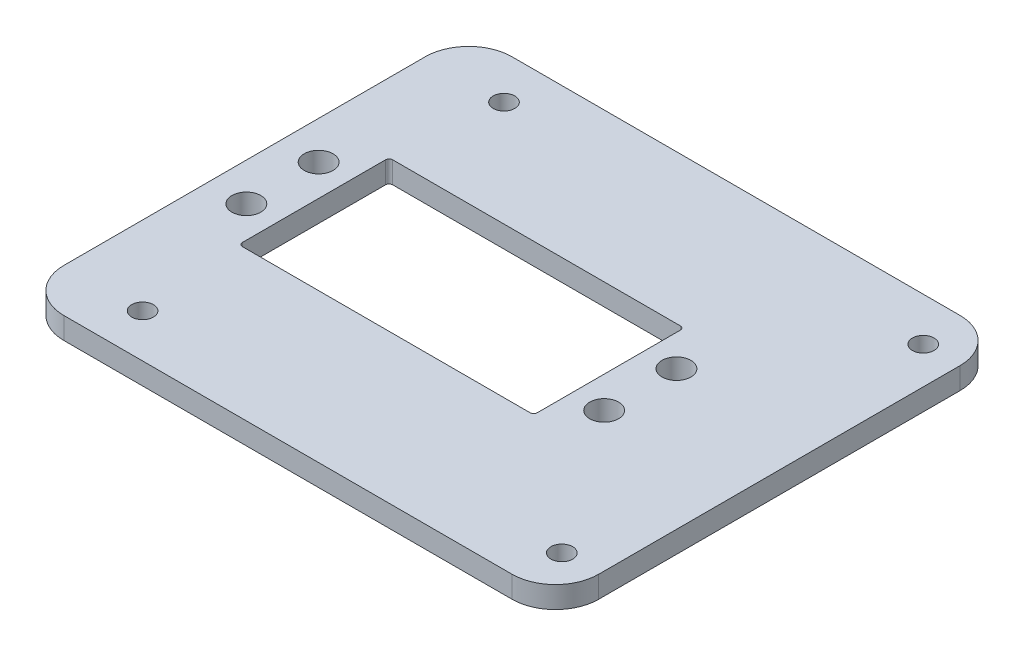
SolidWorks part; units mm, degrees
material "Thornel Mat VMA"
ref_plane "前视基准面" through (0, 0, 0) normal (0, 0, 1) x (1, 0, 0)
ref_plane "上视基准面" through (0, 0, 0) normal (0, 1, 0) x (1, 0, 0)
ref_plane "右视基准面" through (0, 0, 0) normal (1, 0, 0) x (0, 0, -1)
other "Configuration Table"
sketch "草图1" plane through (0, 0, 0) normal (0, 1, 0) x (1, 0, 0)
  line L0 (0, 0) -> (0, 29.6725) construction
  line L1 (-30, -31) -> (30, -31)
  line L2 (-30, -31) -> (-30, 31)
  line L3 (-30, 31) -> (30, 31)
  line L4 (30, -31) -> (30, 31)
  line L5 (-30, -31) -> (30, 31) construction
  line L6 (-30, 31) -> (30, -31) construction
  line L11 (-15.5388, -16.0567) -> (15.4817, 15.9977) construction
  line L12 (9.89, 0) -> (9.89, 37.58) construction
  line L13 (-20.4, -10.4) -> (20.4, -10.4)
  line L14 (-20.4, -10.4) -> (-20.4, 10.4)
  line L15 (-20.4, 10.4) -> (20.4, 10.4)
  line L16 (20.4, -10.4) -> (20.4, 10.4)
  line L17 (-20.4, -10.4) -> (20.4, 10.4) construction
  line L18 (-20.4, 10.4) -> (20.4, -10.4) construction
  line L19 (0, 0) -> (43.0948, 0) construction
  line L20 (30, 31) -> (44, 31)
  line L21 (44, 31) -> (44, -31)
  line L22 (30, -31) -> (44, -31)
  circle A0 centre (24.75, 5) radius 2
  circle A1 centre (24.75, -5) radius 2
  circle A2 centre (-24.75, -5) radius 2
  circle A3 centre (-24.75, 5) radius 2
  circle A8 centre (-19.11, 25) radius 1.5
  circle A9 centre (-19.11, -25) radius 1.5
  circle A10 centre (38.89, -25) radius 1.5
  circle A11 centre (38.89, 25) radius 1.5
  point P0 (0, 0)
  point P6 (0, 0)
  point P13 (0, 0)
  point P38 (44, 0)
  dimension "D5" = 4
  dimension "D8" = 9.89
  dimension "D7" = 49.5
  dimension "D9" = 3
  dimension "D10" = 25
  dimension "D1" = 60
  dimension "D2" = 62
  dimension "D3" = 40.8
  dimension "D4" = 20.8
  dimension "D6" = 5
  dimension "D11" = 29
  dimension "D12" = 14
extrude "凸台-拉伸1" add sketch "草图1" along normal blind 3 contours L1 L4 L3 L2 A3 A2 L16 L13 L14 L15 A0 A1 A8 A9 | L4 L22 L21 L20 A10 A11
fillet "圆角1" radius 0.5 4 edges at (20.4, 1.5, 10.4) (-20.4, 1.5, 10.4) (20.4, 1.5, -10.4) (-20.4, 1.5, -10.4)
fillet "圆角2" radius 6 4 edges at (44, 1.5, -31) (44, 1.5, 31) (-30, 1.5, 31) (-30, 1.5, -31)
